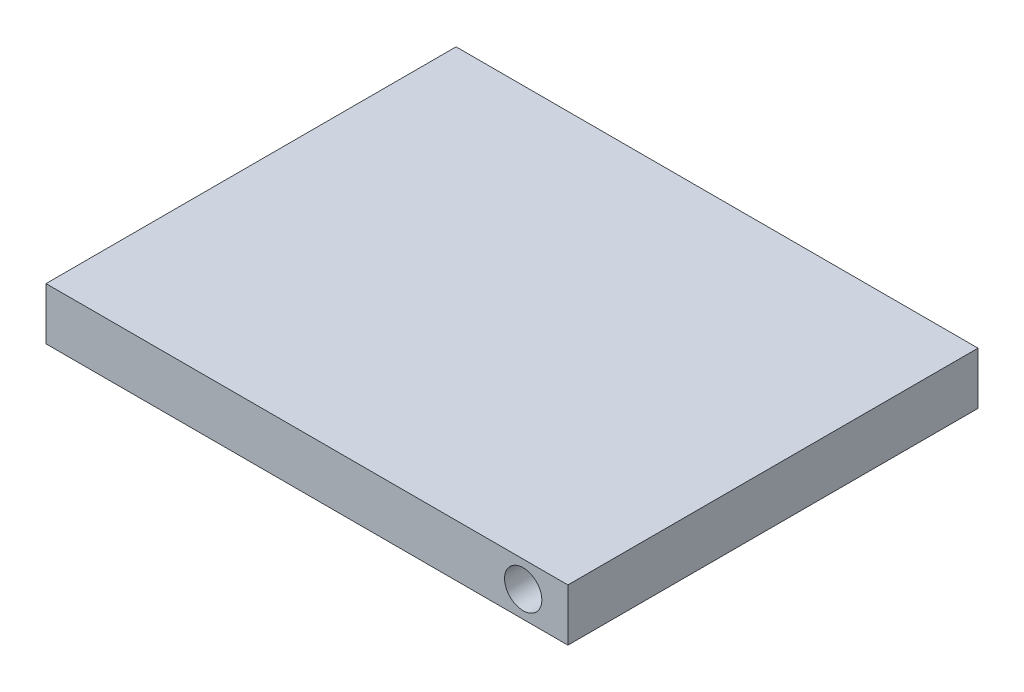
SolidWorks part; units mm, degrees
ref_plane "Front Plane" through (0, 0, 0) normal (0, 0, 1) x (1, 0, 0)
ref_plane "Top Plane" through (0, 0, 0) normal (0, 1, 0) x (1, 0, 0)
ref_plane "Right Plane" through (0, 0, 0) normal (1, 0, 0) x (0, 0, -1)
sketch "Sketch1" plane through (0, 0, 0) normal (0, 1, 0) x (1, 0, 0)
  line L1 (0, 0) -> (70, 0)
  line L2 (0, 0) -> (0, 55)
  line L3 (0, 55) -> (70, 55)
  line L4 (70, 0) -> (70, 55)
  dimension "D1" = 55
  dimension "D2" = 70
extrude "Boss-Extrude1" add sketch "Sketch1" along normal blind 7
sketch "Sketch2" plane through (0, 0, -55) normal (0, 0, -1) x (-1, 0, 0)
  line L0 (-70, 7) -> (-64, 7)
  line L1 (-70, 7) -> (0, 7) construction
  line L2 (-64, 7) -> (-64, 0)
  line L3 (-70, 0) -> (0, 0) construction
  circle A0 centre (-64, 3.5) radius 2.5
  dimension "D2" = 5
  dimension "D1" = 6
extrude "Cut-Extrude1" cut sketch "Sketch2" against normal blind 100 contours L2 A0 | L2 A0
